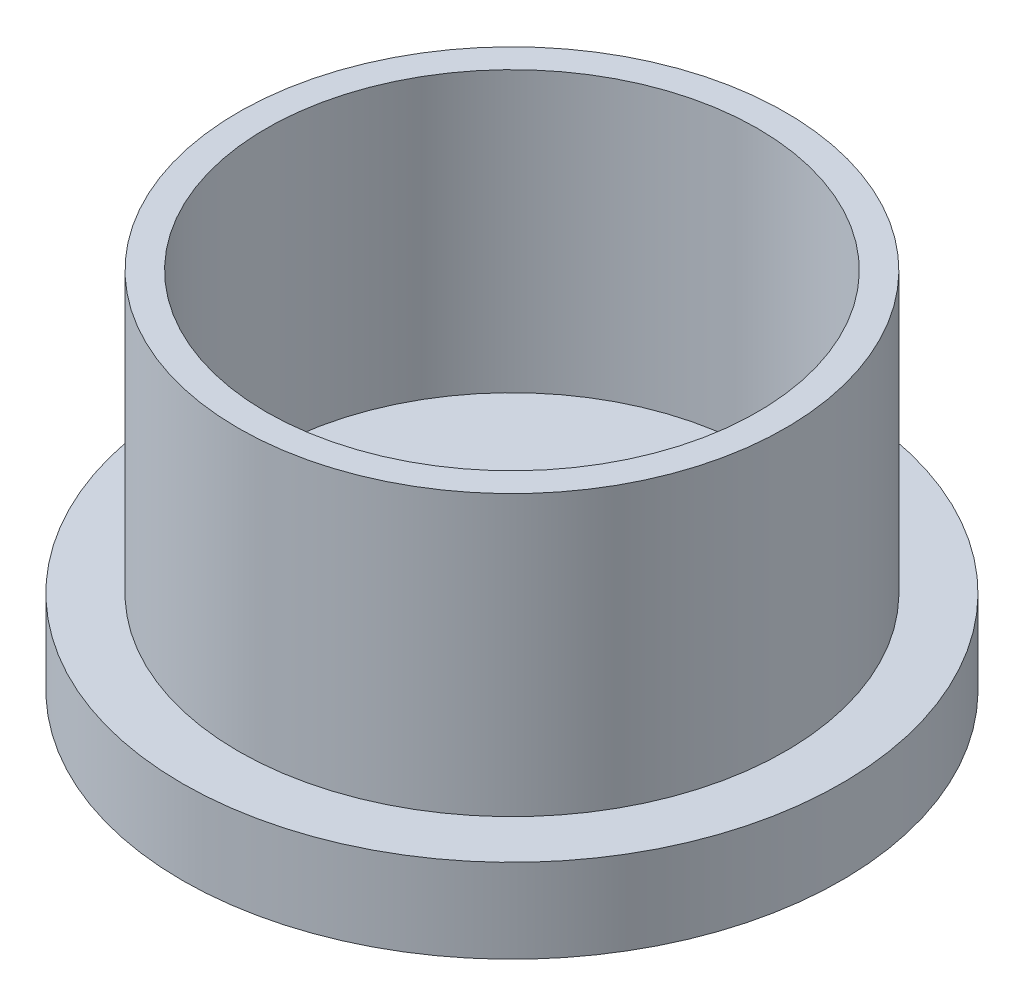
SolidWorks part; units mm, degrees
ref_plane "Front Plane" through (0, 0, 0) normal (0, 0, 1) x (1, 0, 0)
ref_plane "Top Plane" through (0, 0, 0) normal (0, 1, 0) x (1, 0, 0)
ref_plane "Right Plane" through (0, 0, 0) normal (1, 0, 0) x (0, 0, -1)
sketch "Sketch1" plane through (0, 0, 0) normal (0, 1, 0) x (1, 0, 0)
  circle A0 centre (0, 0) radius 11.78
  point P3 (0, 0)
  dimension "D1" = 23.56
extrude "Boss-Extrude1" add sketch "Sketch1" along normal blind 3
sketch "Sketch3" plane through (0, 3, 0) normal (0, 1, 0) x (1, 0, 0)
  line L1 (-7.78, 0.75) -> (7.78, 0.75)
  line L2 (-7.78, 0.75) -> (-7.78, -0.75)
  line L3 (-7.78, -0.75) -> (7.78, -0.75)
  line L4 (7.78, 0.75) -> (7.78, -0.75)
  line L5 (-7.78, 0.75) -> (7.78, -0.75) construction
  line L6 (-7.78, -0.75) -> (7.78, 0.75) construction
  point P0 (0, 0)
  dimension "D1" = 1.5
  dimension "D2" = 15.56
extrude "Cut-Extrude1" cut sketch "Sketch3" against normal blind 3 contours L3 L4 L1 L2
sketch "Sketch4" plane through (0, 3, 0) normal (0, 1, 0) x (1, 0, 0)
  line L1 (-0.75, 7.78) -> (0.75, 7.78)
  line L2 (-0.75, 7.78) -> (-0.75, -7.78)
  line L3 (-0.75, -7.78) -> (0.75, -7.78)
  line L4 (0.75, 7.78) -> (0.75, -7.78)
  line L5 (-0.75, 7.78) -> (0.75, -7.78) construction
  line L6 (-0.75, -7.78) -> (0.75, 7.78) construction
  point P0 (0, 0)
  dimension "D1" = 1.5
  dimension "D2" = 15.56
extrude "Cut-Extrude2" cut sketch "Sketch4" against normal blind 3
sketch "Sketch5" plane through (0, 3, 0) normal (0, 1, 0) x (1, 0, 0)
  circle A0 centre (0, 0) radius 9.78
  dimension "D1" = 19.56
extrude "Boss-Extrude3" add sketch "Sketch5" along normal blind 10
sketch "Sketch6" plane through (0, 13, 0) normal (0, 1, 0) x (1, 0, 0)
  circle A0 centre (0, 0) radius 8.78
  dimension "D1" = 17.56
extrude "Cut-Extrude3" cut sketch "Sketch6" against normal blind 10
